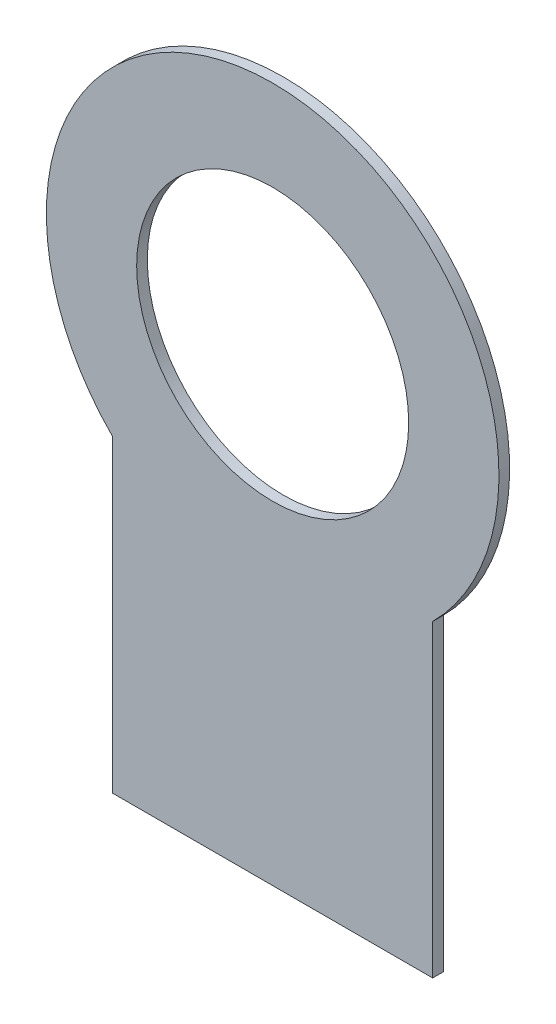
SolidWorks part; units mm, degrees
ref_plane "前视基准面" through (0, 0, 0) normal (0, 0, 1) x (1, 0, 0)
ref_plane "上视基准面" through (0, 0, 0) normal (0, 1, 0) x (1, 0, 0)
ref_plane "右视基准面" through (0, 0, 0) normal (1, 0, 0) x (0, 0, -1)
other "Configuration Table"
sketch "草图1" plane through (0, 0, 0) normal (0, 0, 1) x (1, 0, 0)
  line L0 (-30, -87.8915) -> (30.1464, -87.8915) construction
  line L1 (-30, -87.8915) -> (30, -87.8915)
  line L2 (-30, -87.8915) -> (-30, 30)
  line L3 (-30, 30) -> (30, 30)
  line L4 (30, -87.8915) -> (30, 30)
  line L5 (-30, -87.8915) -> (-30, -65) construction
  circle A0 centre (0, 0) radius 25.5
  circle A1 centre (0, 0) radius 42.4264
extrude "凸台-拉伸1" add sketch "草图1" along normal blind 2 contours A1 L2 L1 L4 | L2 A1 L4 L3 A0 | L2 A1 | L4 A1 | L3 A1
